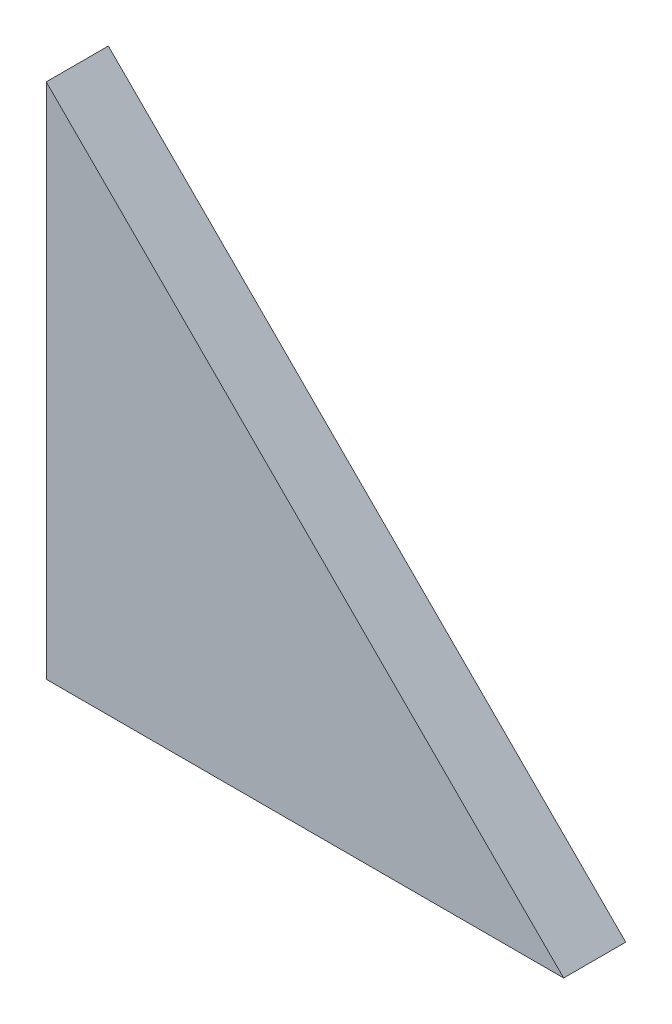
SolidWorks part; units mm, degrees
material "MDF"
ref_plane "Alzado" through (0, 0, 0) normal (0, 0, 1) x (1, 0, 0)
ref_plane "Planta" through (0, 0, 0) normal (0, 1, 0) x (1, 0, 0)
ref_plane "Vista lateral" through (0, 0, 0) normal (1, 0, 0) x (0, 0, -1)
sketch "Croquis1" plane through (0, 0, 0) normal (0, 0, 1) x (1, 0, 0)
  line L0 (0, 25) -> (25, 0)
  line L2 (0, 25) -> (0, 0)
  line L3 (0, 0) -> (25, 0)
  line L5 (0, 25) -> (25, 0) construction
  point P0 (0, 0)
  dimension "D1" = 25
  dimension "D2" = 25
extrude "Saliente-Extruir1" add sketch "Croquis1" along normal mid plane 3
